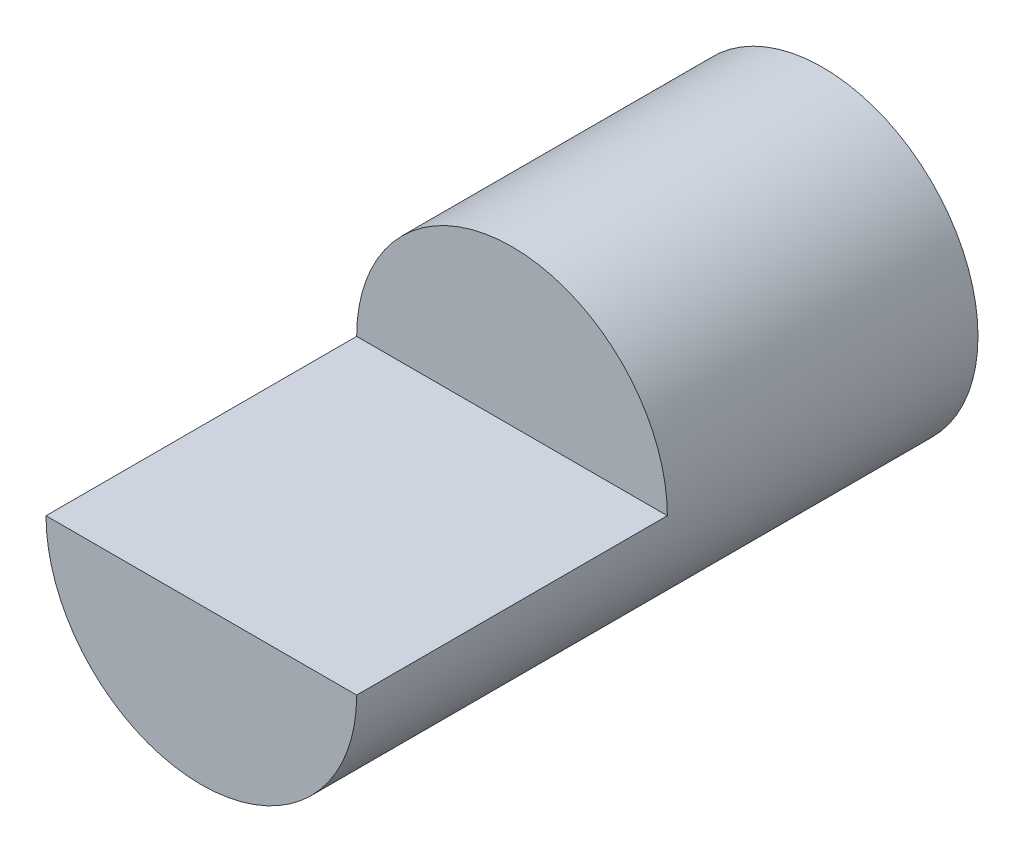
SolidWorks part; units mm, degrees
ref_plane "Front Plane" through (0, 0, 0) normal (0, 0, 1) x (1, 0, 0)
ref_plane "Top Plane" through (0, 0, 0) normal (0, 1, 0) x (1, 0, 0)
ref_plane "Right Plane" through (0, 0, 0) normal (1, 0, 0) x (0, 0, -1)
sketch "Sketch1" plane through (0, 0, 0) normal (0, 0, 1) x (1, 0, 0)
  circle A0 centre (0, 0) radius 6.35
  dimension "D1" = 12.7
extrude "Boss-Extrude1" add sketch "Sketch1" along normal blind 12.7
ref_plane "Plane1" through (0, 0, 12.7) normal (0, 0, 1) x (1, 0, 0)
sketch "Sketch2" plane through (0, 0, 12.7) normal (0, 0, 1) x (1, 0, 0)
  line L0 (6.35, 0) -> (-6.35, 0)
  arc A0 (-6.35, 0) -> (6.35, 0) centre (0, 0) ccw
  circle A1 centre (0, 0) radius 6.35 construction
  point P6 (6.3221, -0.5947)
  point P7 (0, 0)
extrude "Boss-Extrude2" add sketch "Sketch2" along normal blind 12.7
